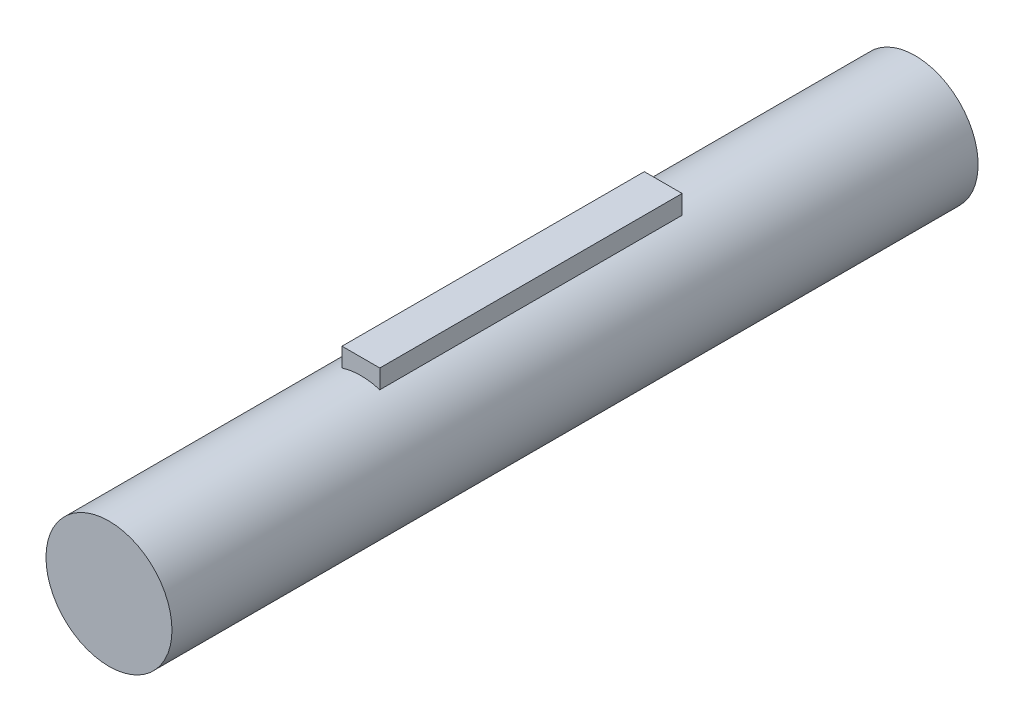
SolidWorks part; units mm, degrees
ref_plane "Front Plane" through (0, 0, 0) normal (0, 0, 1) x (1, 0, 0)
ref_plane "Top Plane" through (0, 0, 0) normal (0, 1, 0) x (1, 0, 0)
ref_plane "Right Plane" through (0, 0, 0) normal (1, 0, 0) x (0, 0, -1)
sketch "Sketch1" plane through (0, 0, 0) normal (0, 0, 1) x (1, 0, 0)
  line L6 (2.3813, 7.5719) -> (2.3812, 9.9531)
  line L7 (2.3812, 9.9531) -> (-2.3813, 9.9531)
  line L8 (-2.3813, 7.5719) -> (-2.3813, 9.9531)
  arc A1 (-2.3813, 7.5719) -> (2.3813, 7.5719) centre (0, 0) ccw
  point P1 (0, 9.9531)
  dimension "D1" = 15.875
  dimension "D2" = 4.7625
  dimension "D3" = 2.3813
extrude "Boss-Extrude1" add sketch "Sketch1" along normal blind 38.1
sketch "Sketch2" plane through (0, 0, 38.1) normal (0, 0, 1) x (1, 0, 0)
  circle A0 centre (0, 0) radius 7.9375
extrude "Boss-Extrude2" add sketch "Sketch2" along normal blind 31.75
sketch "Sketch3" plane through (0, 0, 0) normal (0, 0, -1) x (-1, 0, 0)
  circle A0 centre (0, 0) radius 7.9375
extrude "Boss-Extrude3" add sketch "Sketch3" along normal blind 31.75
